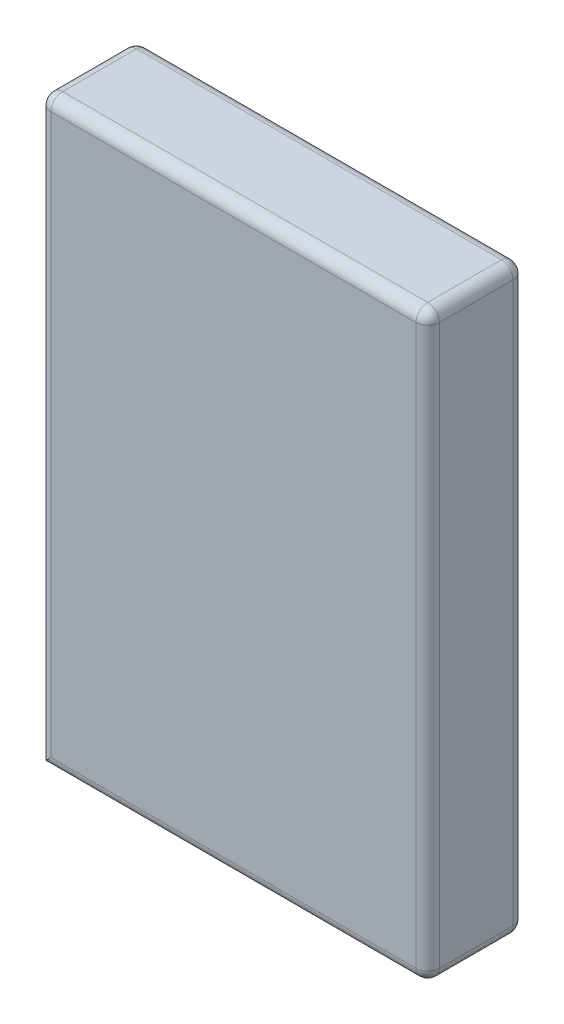
SolidWorks part; units mm, degrees
ref_plane "Front Plane" through (0, 0, 0) normal (0, 0, 1) x (1, 0, 0)
ref_plane "Top Plane" through (0, 0, 0) normal (0, 1, 0) x (1, 0, 0)
ref_plane "Right Plane" through (0, 0, 0) normal (1, 0, 0) x (0, 0, -1)
sketch "Sketch1" plane through (0, 0, 0) normal (0, 0, 1) x (1, 0, 0)
  line L1 (12.7, -19.05) -> (-12.7, -19.05)
  line L2 (12.7, -19.05) -> (12.7, 19.05)
  line L3 (12.7, 19.05) -> (-12.7, 19.05)
  line L4 (-12.7, -19.05) -> (-12.7, 19.05)
  line L5 (12.7, -19.05) -> (-12.7, 19.05) construction
  line L6 (12.7, 19.05) -> (-12.7, -19.05) construction
  point P0 (0, 0)
  dimension "D1" = 25.4
  dimension "D2" = 38.1
extrude "Boss-Extrude1" add sketch "Sketch1" along normal blind 6.35
fillet "Fillet1" radius 0.762 11 edges at (0, -19.05, 6.35) (-12.7, 0, 6.35) (0, 19.05, 6.35) (-12.7, 19.05, 3.175) (0, -19.05, 0) (0, 19.05, 0) (-12.7, 0, 0) (12.7, -19.05, 3.175) (12.7, 0, 6.35) (12.7, 19.05, 3.175) (12.7, 0, 0)
